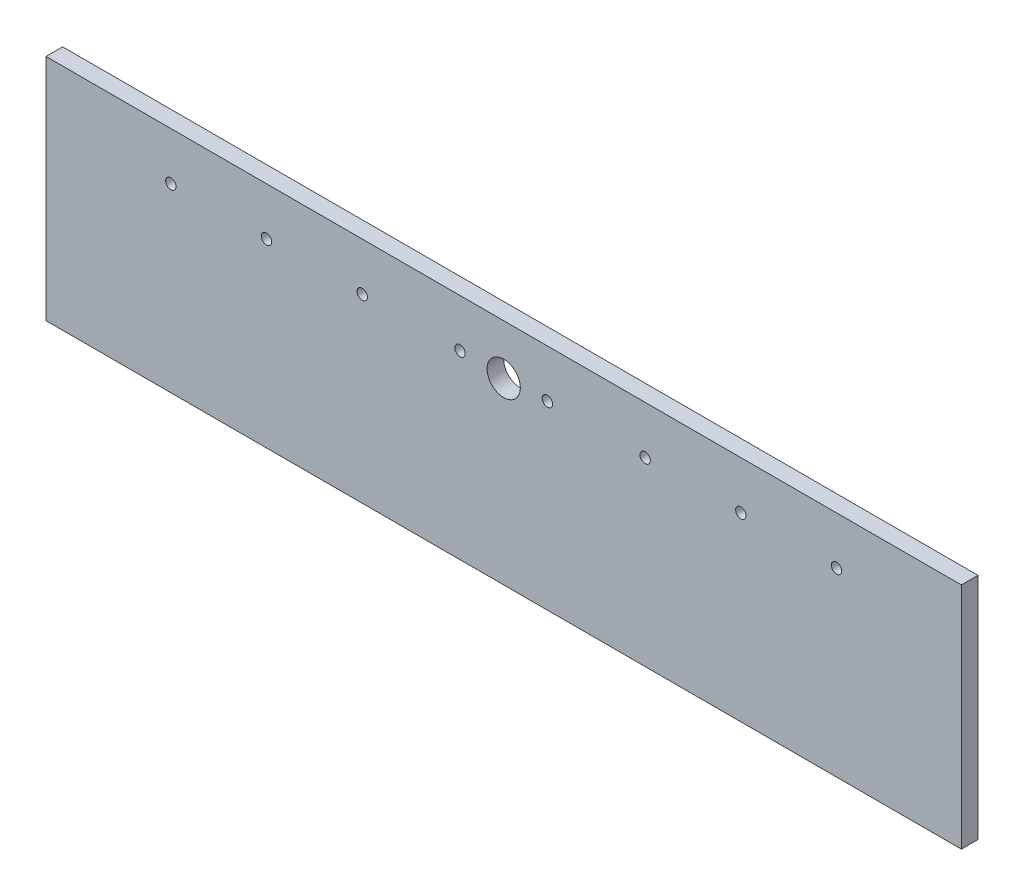
SolidWorks part; units mm, degrees
ref_plane "Front Plane" through (0, 0, 0) normal (0, 0, 1) x (1, 0, 0)
ref_plane "Top Plane" through (0, 0, 0) normal (0, 1, 0) x (1, 0, 0)
ref_plane "Right Plane" through (0, 0, 0) normal (1, 0, 0) x (0, 0, -1)
sketch "Sketch1" plane through (0, 0, 0) normal (0, 0, 1) x (1, 0, 0)
  line L0 (698.5, 349.25) -> (698.5, 0) construction
  line L1 (0, 0) -> (1397, 0)
  line L2 (0, 0) -> (0, 349.25)
  line L3 (0, 349.25) -> (1397, 349.25)
  line L4 (1397, 0) -> (1397, 349.25)
  circle A0 centre (698.5, 273.05) radius 25.4
  circle A1 centre (190.5, 276.225) radius 7.9375
  circle A2 centre (336.55, 276.225) radius 7.9375
  circle A3 centre (482.6, 276.225) radius 7.9375
  circle A4 centre (631.825, 276.225) radius 7.9375
  circle A5 centre (1206.5, 276.225) radius 7.9375
  circle A6 centre (1060.45, 276.225) radius 7.9375
  circle A7 centre (914.4, 276.225) radius 7.9375
  circle A8 centre (765.175, 276.225) radius 7.9375
  point P8 (698.5, 0)
  dimension "D3" = 50.8
  dimension "D10" = 15.875
  dimension "D1" = 349.25
  dimension "D2" = 1397
  dimension "D4" = 76.2
  dimension "D5" = 190.5
  dimension "D6" = 336.55
  dimension "D7" = 482.6
  dimension "D8" = 631.825
  dimension "D9" = 73.025
extrude "Boss-Extrude1" add sketch "Sketch1" along normal blind 25.4
